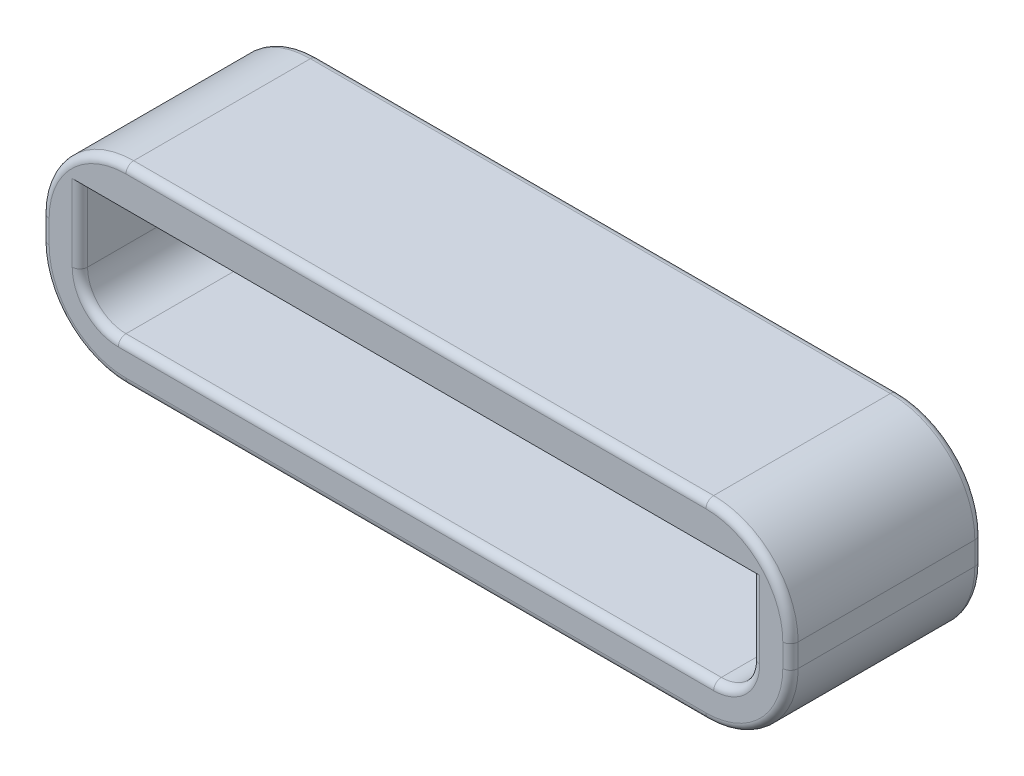
SolidWorks part; units mm, degrees
ref_plane "Front" through (0, 0, 0) normal (0, 0, 1) x (1, 0, 0)
ref_plane "Top" through (0, 0, 0) normal (0, 1, 0) x (1, 0, 0)
ref_plane "Right" through (0, 0, 0) normal (1, 0, 0) x (0, 0, -1)
sketch "Эскиз1" plane through (0, 0, 0) normal (0, 0, 1) x (1, 0, 0)
  line L0 (-9.75, 2.5) -> (9.75, 2.5)
  line L1 (-8.75, -1.5) -> (8.75, -1.5)
  line L2 (-8.75, -1.5) -> (-8.75, 1.5)
  line L3 (-8.75, 1.5) -> (8.75, 1.5)
  line L4 (8.75, -1.5) -> (8.75, 1.5)
  line L5 (-8.75, -1.5) -> (8.75, 1.5) construction
  line L6 (-8.75, 1.5) -> (8.75, -1.5) construction
  line L7 (9.75, -2.5) -> (9.75, 2.5)
  line L8 (-9.75, -2.5) -> (9.75, -2.5)
  line L9 (-9.75, -2.5) -> (-9.75, 2.5)
  point P0 (0, 0)
  dimension "D1" = 17.5
  dimension "D2" = 3
  dimension "D3" = 1
extrude "Бобышка-Вытянуть1" add sketch "Эскиз1" along normal blind 5
fillet "Скругление1" radius 2.2 4 edges at (9.75, 2.5, 2.5) (-9.75, 2.5, 2.5) (-9.75, -2.5, 2.5) (9.75, -2.5, 2.5)
fillet "Скругление2" radius 1 2 edges at (-8.75, -1.5, 2.5) (8.75, -1.5, 2.5)
fillet "Скругление3" radius 0.2 26 edges at (-8.75, 0.5, 5) (-8.4571, -1.2071, 5) (8.75, 0.5, 5) (8.4571, -1.2071, 5) (-8.75, 0.5, 0) (-8.4571, -1.2071, 0) (8.75, 0.5, 0) (8.4571, -1.2071, 0) (-9.1056, -1.8556, 5) (-9.75, 0, 5) (-9.1056, 1.8556, 5) (0, 2.5, 5) (9.1056, 1.8556, 5) (9.75, 0, 5) (9.1056, -1.8556, 5) (-9.1056, -1.8556, 0) (-9.75, 0, 0) (-9.1056, 1.8556, 0) (0, 2.5, 0) (9.1056, 1.8556, 0) (9.75, 0, 0) (9.1056, -1.8556, 0) (0, -1.5, 5) (0, -1.5, 0) (0, -2.5, 5) (0, -2.5, 0)
